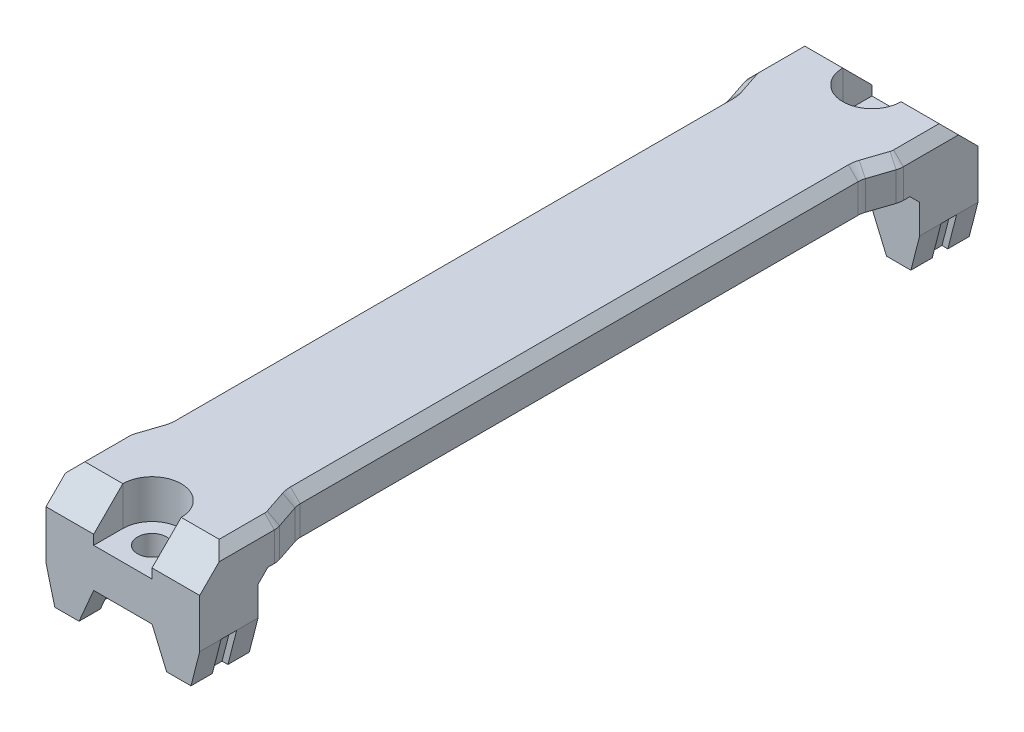
SolidWorks part; units mm, degrees
material "ABS"
ref_plane "正面" through (0, 0, 0) normal (0, 0, 1) x (1, 0, 0)
ref_plane "平面" through (0, 0, 0) normal (0, 1, 0) x (1, 0, 0)
ref_plane "右側面" through (0, 0, 0) normal (1, 0, 0) x (0, 0, -1)
sketch "ｽｹｯﾁ1" plane through (0, 0, 0) normal (0, 1, 0) x (1, 0, 0)
  line L2 (-7.9, 0) -> (-7.9, -48)
  line L3 (-7.9, -48) -> (7.9, -48)
  line L4 (7.9, 0) -> (7.9, -48)
  line L5 (-7.9, 0) -> (7.9, -48) construction
  line L6 (-7.9, -48) -> (7.9, 0) construction
  arc A0 (7.9, 0) -> (-7.9, 0) centre (0, 0) ccw
  point P7 (0, -24)
  dimension "D4" = 48
  dimension "D3" = 15.8
extrude "ﾎﾞｽ - 押し出し1" add sketch "ｽｹｯﾁ1" along normal blind 4
sketch "ｽｹｯﾁ4" plane through (0, 0, 48) normal (0, 0, 1) x (1, 0, 0)
  line L1 (-7, -7.5) -> (-4.5, -7.5)
  line L2 (-4.5, -7.5) -> (-3, -4)
  line L3 (-3, -4) -> (3, -4)
  line L4 (3, -4) -> (4.5, -7.5)
  line L5 (4.5, -7.5) -> (7, -7.5)
  line L7 (7.9, 0) -> (-7.9, 0)
  line L8 (-7, -7.5) -> (-7.9, -4)
  line L9 (-7.9, -4) -> (-7.9, 0)
  line L10 (7.9, 0) -> (7.9, -4)
  line L11 (7.9, -4) -> (7, -7.5)
  dimension "D1" = 7.5
  dimension "D2" = 3.5
  dimension "D3" = 3
  dimension "D4" = 7
  dimension "D5" = 2.5
  dimension "D9" = 4
  dimension "D10" = 4
extrude "ﾎﾞｽ - 押し出し3" add sketch "ｽｹｯﾁ4" against normal blind 6
chamfer "面取り1" distance 3 angle 45 1 edges at (0, 4, 48)
sketch "ｽｹｯﾁ6" plane through (0, 4, 0) normal (0, 1, 0) x (1, 0, 0)
  line L0 (-3, -45) -> (-3, -49)
  line L1 (-3, -49) -> (3, -49)
  line L2 (3, -49) -> (3, -45)
  line L3 (7.9, -48) -> (-7.9, -48) construction
  arc A0 (3, -45) -> (-3, -45) centre (0, -45) ccw
  dimension "D1" = 6
  dimension "D3" = 3
  dimension "D2" = 0
  dimension "D4" = 4
extrude "ｶｯﾄ - 押し出し2" cut sketch "ｽｹｯﾁ6" against normal blind 3.99
sketch "ｽｹｯﾁ7" plane through (0, 0.01, 0) normal (0, 1, 0) x (1, 0, 0)
  circle A0 centre (0, -45) radius 1.5
  dimension "D1" = 3
extrude "ｶｯﾄ - 押し出し3" cut sketch "ｽｹｯﾁ7" against normal up to next
sketch "ｽｹｯﾁ8" plane through (0, 0, 0) normal (0, -1, 0) x (1, 0, 0)
  circle A0 centre (0, 0) radius 6
  dimension "D1" = 12
extrude "ﾎﾞｽ - 押し出し4" add sketch "ｽｹｯﾁ8" along normal blind 1
fillet "ﾌｨﾚｯﾄ1" radius 0.5 1 edges at (0, 0, 6)
sketch "ｽｹｯﾁ9" plane through (0, 4, 0) normal (0, 1, 0) x (1, 0, 0)
  circle A0 centre (0, 0) radius 5
  dimension "D1" = 10
extrude "ｶｯﾄ - 押し出し4" cut sketch "ｽｹｯﾁ9" against normal blind 3
sketch "ｽｹｯﾁ10" plane through (0, 1, 0) normal (0, 1, 0) x (1, 0, 0)
  circle A0 centre (0, 0) radius 3.55
  dimension "D1" = 7.1
extrude "ｶｯﾄ - 押し出し5" cut sketch "ｽｹｯﾁ10" against normal blind 3.6
ref_plane "平面1" through (0, 0, 45) normal (0, 0, 1) x (1, 0, 0)
sketch "ｽｹｯﾁ11" plane through (0, 0, 45) normal (0, 0, 1) x (1, 0, 0)
  line L0 (3, -4) -> (4.5, -7.5)
  line L1 (3, -4) -> (3.6, -4)
  line L2 (4.5, -7.5) -> (5.1, -7.5)
  line L3 (3.6, -4) -> (5.1, -7.5)
  line L4 (3, -4) -> (5.1, -7.5) construction
  line L5 (4.5, -7.5) -> (3.6, -4) construction
  line L6 (-3, -4) -> (3, -4) construction
  line L7 (4.5, -7.5) -> (7, -7.5) construction
  line L8 (6.4, -7.5) -> (7, -7.5)
  line L9 (6.4, -7.5) -> (7.3, -4)
  line L10 (7, -7.5) -> (7.9, -4)
  line L11 (7.3, -4) -> (7.9, -4)
  line L12 (6.4, -7.5) -> (7.9, -4) construction
  line L13 (7, -7.5) -> (7.3, -4) construction
  point P5 (4.05, -5.75)
  point P18 (7.15, -5.75)
  dimension "D1" = 0.6
extrude "ｶｯﾄ - 押し出し6" cut sketch "ｽｹｯﾁ11" against normal mid plane 1.6
mirror "ﾐﾗｰ1" about plane through (0, 0, 0) normal (1, 0, 0) of "ｶｯﾄ - 押し出し6"
sketch "ｽｹｯﾁ12" plane through (0, 4, 0) normal (0, 1, 0) x (1, 0, 0)
  line L0 (-7.9, 0) -> (-7.9, -40)
  line L1 (-7.9, 0) -> (-7.9, -45) construction
  line L2 (-7.9, -40) -> (-6.9, -37)
  line L3 (-6.9, -37) -> (-6.9, -3.8471)
  line L4 (7.9, -48) -> (3, -48) construction
  arc A0 (-7.9, 0) -> (-6.9, -3.8471) centre (0, 0) ccw
  arc A1 (7.9, 0) -> (-7.9, 0) centre (0, 0) ccw construction
  dimension "D1" = 6.9
  dimension "D2" = 3
  dimension "D3" = 11
extrude "ｶｯﾄ - 押し出し7" cut sketch "ｽｹｯﾁ12" against normal through all
mirror "ﾐﾗｰ2" about plane through (0, 0, 0) normal (1, 0, 0) of "ｶｯﾄ - 押し出し7"
fillet "ﾌｨﾚｯﾄ2" radius 2 6 edges at (6.9, 2, 3.8471) (7.9, 2, 40) (6.9, 2, 37) (-7.9, 2, 40) (-6.9, 2, 37) (-6.9, 2, 3.8471)
chamfer "面取り2" distance 1 angle 45 14 edges at (-7.9, 4, 42.6623) (0, 4, -7.9) (7.9, 4, 42.6623) (0, 0, 42) (-7.8742, 4, 40.0042) (-7.4, 4, 38.5) (-6.9258, 4, 36.9958) (-6.9, 4, 20.5057) (-6.9512, 4, 3.8864) (6.9512, 4, 3.8864) (6.9, 4, 20.5057) (6.9258, 4, 36.9958) (7.4, 4, 38.5) (7.8742, 4, 40.0042)
ref_plane "平面2" through (0, 0, 8) normal (0, 0, 1) x (1, 0, 0)
other "ｻｰﾌｪｽ ｶｯﾄ1"
mirror "ﾐﾗｰ4" about plane through (0, 0, 8) normal (0, 0, 1) of bodies 117
